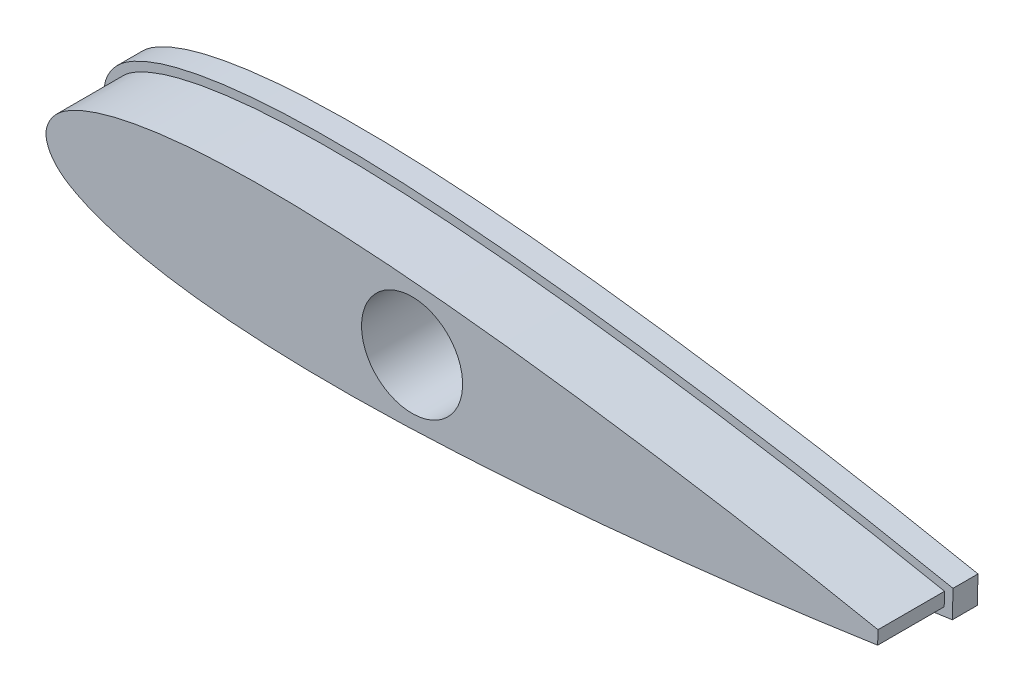
SolidWorks part; units mm, degrees
ref_plane "Alzado" through (0, 0, 0) normal (0, 0, 1) x (1, 0, 0)
ref_plane "Planta" through (0, 0, 0) normal (0, 1, 0) x (1, 0, 0)
ref_plane "Vista lateral" through (0, 0, 0) normal (1, 0, 0) x (0, 0, -1)
sketch "Croquis2" plane through (0, 0, 0) normal (0, 0, 1) x (1, 0, 0)
  line L0 (49.9979, -2.5724) -> (50.0391, -0.9347)
  line L1 (50.9764, -3.44) -> (51.06, -0.1174)
  spline S0 degree 3 poles (51.06, -0.1174) (46.8544, 0.7156) (38.4381, 2.3468) (25.7404, 4.4676) (15.1314, 6.0229) (6.6149, 7.1096) (0.2121, 7.8302) (-6.2093, 8.4419) (-12.6521, 8.9105) (-19.1173, 9.2006) (-24.5253, 9.2504) (-28.8644, 9.1323) (-32.124, 8.9472) (-35.3882, 8.6479) (-38.6607, 8.1982) (-41.3824, 7.6569) (-43.5645, 7.0802) (-45.2154, 6.5315) (-46.8358, 5.8367) (-48.4581, 4.9685) (-49.8909, 3.684) (-50.7371, 2.1799) (-51.06, 0.7913) (-50.8073, -0.6119) (-50.0379, -2.1567) (-48.6716, -3.5117) (-47.095, -4.4604) (-45.5117, -5.2358) (-43.8904, -5.8669) (-41.7402, -6.5527) (-39.0491, -7.2303) (-35.8035, -7.844) (-32.5584, -8.3072) (-29.3123, -8.6561) (-24.9846, -8.9924) (-19.581, -9.2148) (-13.1093, -9.2504) (-6.6511, -9.1066) (-0.207, -8.8188) (6.2239, -8.4213) (14.7843, -7.7646) (25.4581, -6.7451) (38.2464, -5.2659) (46.7342, -4.0603) (50.9764, -3.44) knots -0.007442 -0.007442 -0.007442 -0.007442 0.055988 0.119418 0.182849 0.214564 0.246279 0.277994 0.309709 0.341424 0.373139 0.388997 0.404855 0.420712 0.43657 0.452427 0.460356 0.468285 0.476214 0.484142 0.492071 0.496036 0.5 0.503964 0.507929 0.515858 0.523786 0.531715 0.539644 0.547573 0.56343 0.579288 0.595145 0.611003 0.626861 0.658576 0.690291 0.722006 0.753721 0.785436 0.817151 0.880582 0.944012 1.007442 1.007442 1.007442 1.007442
  spline S1 degree 3 poles (50.0391, -0.9347) (45.8736, -0.1096) (37.5325, 1.4915) (24.962, 3.5762) (12.3529, 5.4126) (-0.304, 6.9333) (-10.9006, 7.8379) (-19.4102, 8.2076) (-25.8063, 8.2564) (-31.1436, 8.0373) (-35.4088, 7.6384) (-38.6027, 7.193) (-41.7753, 6.5551) (-44.3969, 5.7973) (-46.4497, 4.9122) (-47.919, 4.1122) (-49.3619, 2.801) (-50.2399, 0.7706) (-49.4651, -1.3014) (-48.0901, -2.6836) (-46.663, -3.5564) (-44.6573, -4.5438) (-42.0771, -5.4325) (-38.9406, -6.2293) (-35.7731, -6.8348) (-31.5334, -7.4478) (-26.2139, -7.9352) (-19.8235, -8.2083) (-11.3061, -8.2673) (-0.6774, -7.897) (12.04, -7.0152) (24.7255, -5.8157) (37.385, -4.3661) (45.7961, -3.1868) (49.9979, -2.5724) knots -0.003281 -0.003281 -0.003281 -0.003281 0.059629 0.122539 0.185449 0.24836 0.31127 0.342725 0.37418 0.405635 0.421362 0.43709 0.452817 0.468545 0.476409 0.484272 0.492136 0.5 0.507864 0.515728 0.523591 0.531455 0.547183 0.56291 0.578638 0.594365 0.62582 0.657275 0.68873 0.75164 0.814551 0.877461 0.940371 1.003281 1.003281 1.003281 1.003281
extrude "Saliente-Extruir1" add sketch "Croquis2" along normal blind 8 contours S1 L0
sketch "Croquis3" plane through (0, 0, 0) normal (0, 0, 1) x (1, 0, 0)
  line L0 (49.9979, -2.5724) -> (50.0391, -0.9347)
  line L1 (50.9764, -3.44) -> (51.06, -0.1174)
  spline S0 degree 3 poles (51.06, -0.1174) (46.8544, 0.7156) (38.4381, 2.3468) (25.7404, 4.4676) (15.1314, 6.0229) (6.6149, 7.1096) (0.2121, 7.8302) (-6.2093, 8.4419) (-12.6521, 8.9105) (-19.1173, 9.2006) (-24.5253, 9.2504) (-28.8644, 9.1323) (-32.124, 8.9472) (-35.3882, 8.6479) (-38.6607, 8.1982) (-41.3824, 7.6569) (-43.5645, 7.0802) (-45.2154, 6.5315) (-46.8358, 5.8367) (-48.4581, 4.9685) (-49.8909, 3.684) (-50.7371, 2.1799) (-51.06, 0.7913) (-50.8073, -0.6119) (-50.0379, -2.1567) (-48.6716, -3.5117) (-47.095, -4.4604) (-45.5117, -5.2358) (-43.8904, -5.8669) (-41.7402, -6.5527) (-39.0491, -7.2303) (-35.8035, -7.844) (-32.5584, -8.3072) (-29.3123, -8.6561) (-24.9846, -8.9924) (-19.581, -9.2148) (-13.1093, -9.2504) (-6.6511, -9.1066) (-0.207, -8.8188) (6.2239, -8.4213) (14.7843, -7.7646) (25.4581, -6.7451) (38.2464, -5.2659) (46.7342, -4.0603) (50.9764, -3.44) knots -0.007442 -0.007442 -0.007442 -0.007442 0.055988 0.119418 0.182849 0.214564 0.246279 0.277994 0.309709 0.341424 0.373139 0.388997 0.404855 0.420712 0.43657 0.452427 0.460356 0.468285 0.476214 0.484142 0.492071 0.496036 0.5 0.503964 0.507929 0.515858 0.523786 0.531715 0.539644 0.547573 0.56343 0.579288 0.595145 0.611003 0.626861 0.658576 0.690291 0.722006 0.753721 0.785436 0.817151 0.880582 0.944012 1.007442 1.007442 1.007442 1.007442
  spline S1 degree 3 poles (50.0391, -0.9347) (45.8736, -0.1096) (37.5325, 1.4915) (24.962, 3.5762) (12.3529, 5.4126) (-0.304, 6.9333) (-10.9006, 7.8379) (-19.4102, 8.2076) (-25.8063, 8.2564) (-31.1436, 8.0373) (-35.4088, 7.6384) (-38.6027, 7.193) (-41.7753, 6.5551) (-44.3969, 5.7973) (-46.4497, 4.9122) (-47.919, 4.1122) (-49.3619, 2.801) (-50.2399, 0.7706) (-49.4651, -1.3014) (-48.0901, -2.6836) (-46.663, -3.5564) (-44.6573, -4.5438) (-42.0771, -5.4325) (-38.9406, -6.2293) (-35.7731, -6.8348) (-31.5334, -7.4478) (-26.2139, -7.9352) (-19.8235, -8.2083) (-11.3061, -8.2673) (-0.6774, -7.897) (12.04, -7.0152) (24.7255, -5.8157) (37.385, -4.3661) (45.7961, -3.1868) (49.9979, -2.5724) knots -0.003281 -0.003281 -0.003281 -0.003281 0.059629 0.122539 0.185449 0.24836 0.31127 0.342725 0.37418 0.405635 0.421362 0.43709 0.452817 0.468545 0.476409 0.484272 0.492136 0.5 0.507864 0.515728 0.523591 0.531455 0.547183 0.56291 0.578638 0.594365 0.62582 0.657275 0.68873 0.75164 0.814551 0.877461 0.940371 1.003281 1.003281 1.003281 1.003281
extrude "Saliente-Extruir2" add sketch "Croquis3" against normal blind 3 contours L1 S0
sketch "Croquis4" plane through (0, 0, -3) normal (0, 0, -1) x (-1, 0, 0)
  line L0 (-51.0182, -1.7787) -> (50.9641, 0.7888) construction
  line L1 (-51.06, -0.1174) -> (-50.9764, -3.44)
  line L2 (-51.06, -0.1174) -> (-50.9764, -3.44) construction
  circle A0 centre (5.9641, -0.3441) radius 6.075
  spline S1 degree 3 poles (-1191.2208, -2745.6699) (-392.3413, 147.7768) (-220.4854, 15.813) (-25.4581, -6.7451) (-14.7843, -7.7646) (-6.2239, -8.4213) (0.207, -8.8188) (6.6511, -9.1066) (13.1093, -9.2504) (19.581, -9.2148) (24.9846, -8.9924) (29.3123, -8.6561) (32.5584, -8.3072) (35.8035, -7.844) (39.0491, -7.2303) (41.7402, -6.5527) (43.8904, -5.8669) (45.5117, -5.2358) (47.095, -4.4604) (48.6716, -3.5117) (50.0379, -2.1567) (50.8073, -0.6119) (51.06, 0.7913) (50.7371, 2.1799) (49.8909, 3.684) (48.4581, 4.9685) (46.8358, 5.8367) (45.2154, 6.5315) (43.5645, 7.0802) (41.3824, 7.6569) (38.6607, 8.1982) (35.3882, 8.6479) (32.124, 8.9472) (28.8644, 9.1323) (24.5253, 9.2504) (19.1173, 9.2006) (12.6521, 8.9105) (6.2093, 8.4419) (-0.2121, 7.8302) (-6.6149, 7.1096) (-15.1314, 6.0229) (-25.7404, 4.4676) (-219.3867, -27.876) (-384.3853, -168.3221) (-1327.8696, 2681.3171) knots -2.719171 -2.719171 -2.719171 -2.719171 0.055988 0.119418 0.182849 0.214564 0.246279 0.277994 0.309709 0.341424 0.373139 0.388997 0.404855 0.420712 0.43657 0.452427 0.460356 0.468285 0.476214 0.484142 0.492071 0.496036 0.5 0.503964 0.507929 0.515858 0.523786 0.531715 0.539644 0.547573 0.56343 0.579288 0.595145 0.611003 0.626861 0.658576 0.690291 0.722006 0.753721 0.785436 0.817151 0.880582 0.944012 3.719189 3.719189 3.719189 3.719189 only from (-50.9764, -3.44) to (-51.06, -0.1174)
  spline S2 degree 3 poles (-50.9764, -3.44) (-46.7342, -4.0603) (-38.2464, -5.2659) (-25.4581, -6.7451) (-14.7843, -7.7646) (-6.2239, -8.4213) (0.207, -8.8188) (6.6511, -9.1066) (13.1093, -9.2504) (19.581, -9.2148) (24.9846, -8.9924) (29.3123, -8.6561) (32.5584, -8.3072) (35.8035, -7.844) (39.0491, -7.2303) (41.7402, -6.5527) (43.8904, -5.8669) (45.5117, -5.2358) (47.095, -4.4604) (48.6716, -3.5117) (50.0379, -2.1567) (50.8073, -0.6119) (51.06, 0.7913) (50.7371, 2.1799) (49.8909, 3.684) (48.4581, 4.9685) (46.8358, 5.8367) (45.2154, 6.5315) (43.5645, 7.0802) (41.3824, 7.6569) (38.6607, 8.1982) (35.3882, 8.6479) (32.124, 8.9472) (28.8644, 9.1323) (24.5253, 9.2504) (19.1173, 9.2006) (12.6521, 8.9105) (6.2093, 8.4419) (-0.2121, 7.8302) (-6.6149, 7.1096) (-15.1314, 6.0229) (-25.7404, 4.4676) (-38.4381, 2.3468) (-46.8544, 0.7156) (-51.06, -0.1174) knots -0.007442 -0.007442 -0.007442 -0.007442 0.055988 0.119418 0.182849 0.214564 0.246279 0.277994 0.309709 0.341424 0.373139 0.388997 0.404855 0.420712 0.43657 0.452427 0.460356 0.468285 0.476214 0.484142 0.492071 0.496036 0.5 0.503964 0.507929 0.515858 0.523786 0.531715 0.539644 0.547573 0.56343 0.579288 0.595145 0.611003 0.626861 0.658576 0.690291 0.722006 0.753721 0.785436 0.817151 0.880582 0.944012 1.007442 1.007442 1.007442 1.007442 construction
  point P6 (0, 0)
  point P7 (0, 0)
  dimension "D2" = 12.15
  dimension "D3" = 45
  dimension "D1" = 0
extrude "Cortar-Extruir1" cut sketch "Croquis4" against normal blind 30
